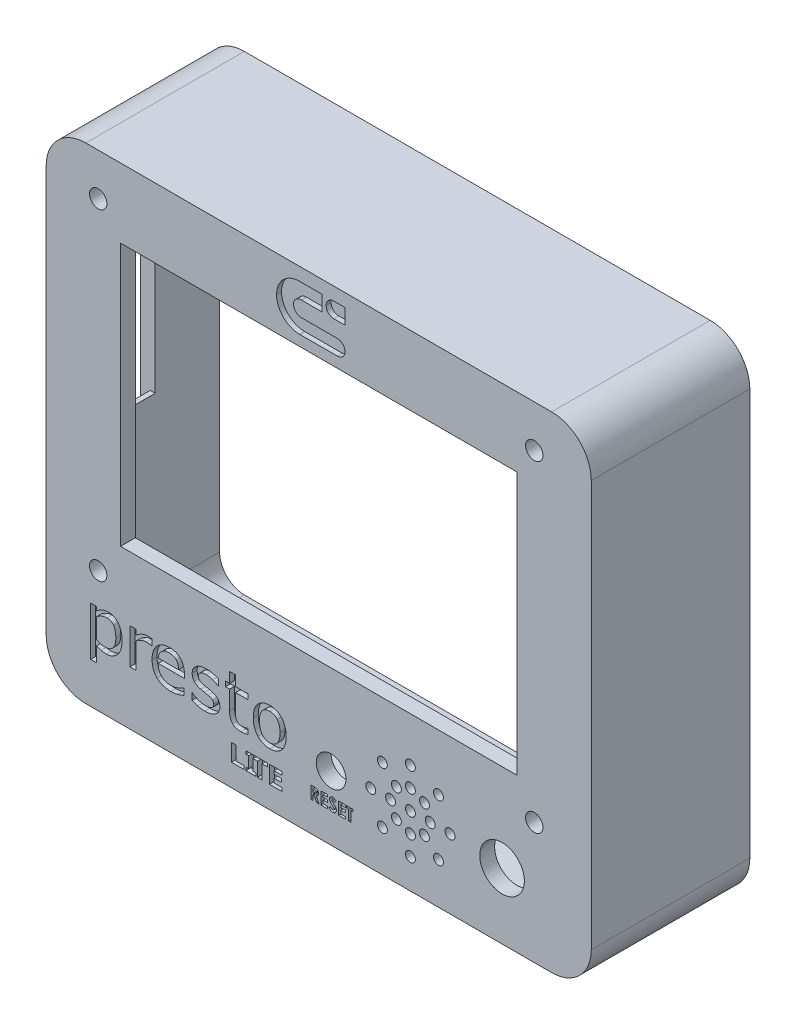
SolidWorks part; units mm, degrees
ref_plane "Plano frontal" through (0, 0, 0) normal (0, 0, 1) x (1, 0, 0)
ref_plane "Plano superior" through (0, 0, 0) normal (0, 1, 0) x (1, 0, 0)
ref_plane "Plano direito" through (0, 0, 0) normal (1, 0, 0) x (0, 0, -1)
sketch "Esboço1" plane through (0, 0, 0) normal (0, 0, 1) x (1, 0, 0)
  line L1 (55, 49) -> (-55, 49)
  line L3 (55, -49) -> (-55, -49)
  line L5 (55, 49) -> (-55, -49) construction
  line L6 (55, -49) -> (-55, 49) construction
  line L13 (-55, 0) -> (55, 0) construction
  line L14 (0, 49) -> (0, -49) construction
  line L38 (55, 49) -> (55, -49)
  line L40 (-55, 49) -> (-55, -49)
  point P0 (0, 0)
  dimension "D1" = 110
  dimension "D2" = 98
extrude "Ressalto-extrusão1" add sketch "Esboço1" along normal blind 22
fillet "Filete1" radius 8 4 edges at (-55, -49, 11) (55, -49, 11) (55, 49, 11) (-55, 49, 11)
shell "Casca1" thickness 3
sketch "Esboço2" plane through (0, 0, 22) normal (0, 0, 1) x (1, 0, 0)
  line L0 (-39, 34) -> (39, 34) construction
  line L1 (-39, 34) -> (-39, -17) construction
  line L2 (-39, -17) -> (39, -17) construction
  line L3 (39, 34) -> (39, -17) construction
  line L4 (-44.5, 40.5) -> (43.5, 40.5) construction
  line L5 (-44.5, 40.5) -> (-44.5, -24.5) construction
  line L6 (-44.5, -24.5) -> (43.5, -24.5) construction
  line L7 (43.5, 40.5) -> (43.5, -24.5) construction
  line L8 (-40, 35) -> (40, 35)
  line L9 (40, 35) -> (40, -18)
  line L10 (-40, -18) -> (40, -18)
  line L11 (-40, 35) -> (-40, -18)
  line L12 (0, 49) -> (0, 35) construction
  line L13 (47, 49) -> (-47, 49) construction
  line L14 (-44.5, 8) -> (43.5, 8) construction
  line L15 (0, 35) -> (0, -18) construction
  line L16 (-0.5, 40.5) -> (-0.5, -24.5) construction
  line L17 (-40, 8.5) -> (40, 8.5) construction
  circle A0 centre (37, -35.75) radius 4.5
  circle A1 centre (2.5, -36) radius 3
  circle A2 centre (-38.5, -33) radius 4 construction
  circle A3 centre (18.5, -35) radius 8
  circle A4 centre (-44.5, 40.5) radius 1.75
  circle A5 centre (43.5, 40.5) radius 1.75
  circle A6 centre (43.5, -24.5) radius 1.75
  circle A7 centre (-44.5, -24.5) radius 1.75
  dimension "D1" = 9
  dimension "D2" = 6
  dimension "D3" = 8
  dimension "D4" = 16
  dimension "D10" = 3.5
  dimension "D5" = 78
  dimension "D6" = 51
  dimension "D7" = 65
  dimension "D8" = 88
  dimension "D11" = 0.5
  dimension "D12" = 0.5
  dimension "D13" = 8.5
  dimension "D14" = 6
  dimension "D15" = 11.5
  dimension "D16" = 3
  dimension "D17" = 10.5
  dimension "D18" = 19
  dimension "D19" = 11.25
  dimension "D20" = 6.5
  dimension "D21" = 14
  dimension "D9" = 1
extrude "Corte-extrusão1" cut sketch "Esboço2" against normal through all contours L8 L11 L10 L9 | A4 | A5 | A6 | A0 | A1 | A2 | A7
sketch "Esboço3" plane through (0, 0, 22) normal (0, 0, 1) x (1, 0, 0)
  line L0 (10.5, -35) -> (26.5, -35) construction
  line L1 (18.5, -27) -> (18.5, -43) construction
  line L2 (12.8431, -40.6569) -> (24.1569, -29.3431) construction
  line L3 (24.1569, -40.6569) -> (12.8431, -29.3431) construction
  circle A0 centre (18.5, -35) radius 1
  circle A1 centre (18.5, -27) radius 1
  circle A2 centre (18.5, -35) radius 8 construction
  circle A3 centre (26.5, -35) radius 1
  circle A4 centre (18.5, -43) radius 1
  circle A5 centre (10.5, -35) radius 1
  circle A6 centre (12.8431, -29.3431) radius 1
  circle A7 centre (24.1569, -29.3431) radius 1
  circle A8 centre (24.1569, -40.6569) radius 1
  circle A9 centre (12.8431, -40.6569) radius 1
  circle A10 centre (18.5, -31) radius 1
  circle A11 centre (21.3284, -32.1716) radius 1
  circle A12 centre (22.5, -35) radius 1
  circle A13 centre (21.3284, -37.8284) radius 1
  circle A14 centre (18.5, -39) radius 1
  circle A15 centre (15.6716, -37.8284) radius 1
  circle A16 centre (14.5, -35) radius 1
  circle A17 centre (15.6716, -32.1716) radius 1
  circle A18 centre (18.5, -35) radius 4 construction
  dimension "D1" = 2
  dimension "D4" = 8
  dimension "D2" = 45
  dimension "D3" = 45
extrude "Corte-extrusão2" cut sketch "Esboço3" against normal blind 10
sketch "Esboço5" plane through (-55, 0, 0) normal (-1, 0, 0) x (0, 0, 1)
  line L0 (22, 8.25) -> (0, 8.25) construction
  line L1 (22, 41) -> (22, -41) construction
  line L2 (0, 41) -> (0, -41) construction
  line L3 (0, 49) -> (22, 49) construction
  line L4 (3, 23.25) -> (9, 23.25)
  line L5 (3, 23.25) -> (3, -6.75)
  line L6 (3, -6.75) -> (9, -6.75)
  line L7 (9, 23.25) -> (9, -6.75)
  line L8 (3, 23.25) -> (9, -6.75) construction
  line L9 (3, -6.75) -> (9, 23.25) construction
  point P8 (6, 8.25)
  dimension "D1" = 25.75
  dimension "D2" = 6
  dimension "D3" = 30
  dimension "D4" = 13
extrude "Corte-extrusão3" cut sketch "Esboço5" against normal blind 4
chamfer "Chanfro1" distance 2 angle 45 3 edges at (-55, -6.75, 6) (-55, 8.25, 9) (-55, 23.25, 6)
sketch "Esboço6" plane through (0, 0, 22) normal (0, 0, 1) x (1, 0, 0)
  line L0 (3.769, 40.2168) -> (0.4907, 40.2168)
  line L1 (0.4907, 40.2168) -> (-3.554, 40.2168)
  line L2 (-3.554, 40.2168) -> (-3.554, 40.2288)
  line L3 (-3.43, 43.3028) -> (0.4898, 43.3028)
  line L4 (0.4898, 43.3028) -> (0.627, 43.3028)
  line L5 (0.627, 43.3028) -> (0.627, 46.3891)
  line L6 (0.627, 46.3891) -> (-3.5708, 46.3891)
  line L7 (-3.5708, 46.3891) -> (-3.5708, 46.378)
  line L8 (-3.769, 37.1306) -> (3.769, 37.1306)
  line L9 (3.0324, 43.3028) -> (5.2847, 43.3028)
  line L10 (5.2847, 43.3028) -> (5.2847, 46.3891)
  line L11 (5.2847, 46.3891) -> (3.0324, 46.3891)
  line L85 (0, 0) -> (0, 56.1921) construction
  spline S0 degree 3 poles (-3.554, 40.2288) (-4.4007, 40.2332) (-5.086, 40.9206) (-5.086, 41.7685) knots 0 0 0 0 1 1 1 1
  spline S1 degree 3 poles (-5.086, 41.7685) (-5.086, 42.6191) (-4.3965, 43.3087) (-3.5458, 43.3087) knots 0 0 0 0 1 1 1 1
  spline S2 degree 3 poles (-3.5458, 43.3087) (-3.5067, 43.3087) (-3.4684, 43.3057) (-3.43, 43.3028) knots 0 0 0 0 1 1 1 1
  spline S3 degree 3 poles (-3.5708, 46.378) (-3.6718, 46.3846) (-3.7734, 46.3891) (-3.8761, 46.3891) knots 0 0 0 0 1 1 1 1
  spline S4 degree 3 poles (-3.8761, 46.3891) (-6.4335, 46.3891) (-8.5066, 44.3158) (-8.5066, 41.7585) knots 0 0 0 0 1 1 1 1
  spline S5 degree 3 poles (-8.5066, 41.7585) (-8.5066, 39.201) (-6.4335, 37.1279) (-3.8761, 37.1279) knots 0 0 0 0 1 1 1 1
  spline S6 degree 3 poles (-3.8761, 37.1279) (-3.8402, 37.1279) (-3.8048, 37.1298) (-3.769, 37.1306) knots 0 0 0 0 1 1 1 1
  spline S7 degree 3 poles (3.769, 37.1306) (4.6213, 37.1306) (5.3122, 37.8214) (5.3122, 38.6738) knots 0 0 0 0 1 1 1 1
  spline S8 degree 3 poles (5.3122, 38.6738) (5.3122, 39.5259) (4.6213, 40.2168) (3.769, 40.2168) knots 0 0 0 0 1 1 1 1
  spline S9 degree 3 poles (3.0324, 46.3891) (2.1802, 46.3891) (1.4893, 45.6981) (1.4893, 44.846) knots 0 0 0 0 1 1 1 1
  spline S10 degree 3 poles (1.4893, 44.846) (1.4893, 43.9937) (2.1802, 43.3028) (3.0324, 43.3028) knots 0 0 0 0 1 1 1 1
extrude "Corte-extrusão4" cut sketch "Esboço6" against normal blind 1
sketch "Esboço7" plane through (0, 0, 22) normal (0, 0, 1) x (1, 0, 0)
  line L12 (-44.8127, -37.7556) -> (-44.8127, -40.7697)
  line L13 (-44.8127, -40.7697) -> (-46.0235, -40.7697)
  line L14 (-46.0235, -40.7697) -> (-46.0235, -30.9222)
  line L15 (-46.0235, -30.9222) -> (-44.8127, -30.9222)
  line L16 (-44.8127, -30.9222) -> (-44.8127, -31.6757)
  line L17 (-44.8127, -32.6933) -> (-44.8127, -36.7702)
  line L18 (-33.6138, -32.2425) -> (-33.6782, -32.2425)
  line L19 (-36.892, -33.0089) -> (-36.892, -38.1162)
  line L20 (-36.892, -38.1162) -> (-38.1028, -38.1162)
  line L21 (-38.1028, -38.1162) -> (-38.1028, -30.9222)
  line L22 (-38.1028, -30.9222) -> (-36.892, -30.9222)
  line L23 (-36.892, -30.9222) -> (-36.892, -31.9849)
  line L24 (-33.6138, -30.9995) -> (-33.6138, -32.2425)
  line L25 (-27.0951, -34.6448) -> (-32.3956, -34.6448)
  line L26 (-27.3012, -36.358) -> (-27.2368, -36.358)
  line L27 (-27.2368, -36.358) -> (-27.2368, -37.6783)
  line L28 (-27.0951, -33.9879) -> (-27.0951, -34.6448)
  line L29 (-32.3956, -33.7174) -> (-28.2737, -33.7174)
  line L30 (-25.5672, -37.6847) -> (-25.5672, -36.3258)
  line L31 (-25.5672, -36.3258) -> (-25.5028, -36.3258)
  line L32 (-20.228, -31.2893) -> (-20.228, -32.5838)
  line L33 (-20.228, -32.5838) -> (-20.2924, -32.5838)
  line L34 (-17.9885, -35.7654) -> (-17.9885, -31.9398)
  line L35 (-17.9885, -31.9398) -> (-18.8064, -31.9398)
  line L36 (-18.8064, -31.9398) -> (-18.8064, -30.9222)
  line L37 (-18.8064, -30.9222) -> (-17.9885, -30.9222)
  line L38 (-17.9885, -30.9222) -> (-17.9885, -28.8548)
  line L39 (-17.9885, -28.8548) -> (-16.7776, -28.8548)
  line L40 (-16.7776, -28.8548) -> (-16.7776, -30.9222)
  line L41 (-16.7776, -30.9222) -> (-14.2787, -30.9222)
  line L42 (-14.2787, -30.9222) -> (-14.2787, -31.9398)
  line L43 (-14.2787, -31.9398) -> (-16.7776, -31.9398)
  line L44 (-16.7776, -31.9398) -> (-16.7776, -35.218)
  line L45 (-14.3431, -36.9634) -> (-14.2787, -36.9634)
  line L46 (-14.2787, -36.9634) -> (-14.2787, -38.0518)
  line L47 (-15.1161, -44.5456) -> (-17.6349, -44.5456)
  line L48 (-17.6349, -44.5456) -> (-17.6349, -41.0536)
  line L49 (-17.6349, -41.0536) -> (-16.7343, -41.0536)
  line L50 (-16.7343, -41.0536) -> (-16.7343, -43.8702)
  line L51 (-16.7343, -43.8702) -> (-15.1161, -43.8702)
  line L52 (-15.1161, -43.8702) -> (-15.1161, -44.5456)
  line L53 (-12.6635, -44.5456) -> (-14.7085, -44.5456)
  line L54 (-14.7085, -44.5456) -> (-14.7085, -43.9265)
  line L55 (-14.7085, -43.9265) -> (-14.1363, -43.9265)
  line L56 (-14.1363, -43.9265) -> (-14.1363, -41.6727)
  line L57 (-14.1363, -41.6727) -> (-14.7085, -41.6727)
  line L58 (-14.7085, -41.6727) -> (-14.7085, -41.0536)
  line L62 (-13.2357, -41.729) -> (-13.2357, -43.9265)
  line L63 (-13.2357, -43.9265) -> (-12.6635, -43.9265)
  line L64 (-12.6635, -43.9265) -> (-12.6635, -44.5456)
  line L65 (-10.3591, -41.729) -> (-11.4496, -41.729)
  line L66 (-11.4496, -41.729) -> (-11.4496, -44.5456)
  line L67 (-11.4496, -44.5456) -> (-12.3502, -44.5456)
  line L68 (-12.3502, -44.5456) -> (-12.3502, -41.729)
  line L69 (-12.3502, -41.729) -> (-13.2357, -41.729)
  line L71 (-14.7085, -41.0536) -> (-10.3591, -41.0536)
  line L72 (-10.3591, -41.0536) -> (-10.3591, -41.729)
  line L73 (-7.3907, -44.5456) -> (-9.9165, -44.5456)
  line L74 (-9.9165, -44.5456) -> (-9.9165, -41.0536)
  line L75 (-9.9165, -41.0536) -> (-7.3907, -41.0536)
  line L76 (-7.3907, -41.0536) -> (-7.3907, -41.729)
  line L77 (-7.3907, -41.729) -> (-9.0206, -41.729)
  line L78 (-9.0206, -41.729) -> (-9.0206, -42.3317)
  line L79 (-9.0206, -42.3317) -> (-7.508, -42.3317)
  line L80 (-7.508, -42.3317) -> (-7.508, -43.0071)
  line L81 (-7.508, -43.0071) -> (-9.0206, -43.0071)
  line L82 (-9.0206, -43.0071) -> (-9.0206, -43.8702)
  line L83 (-9.0206, -43.8702) -> (-7.3907, -43.8702)
  line L84 (-7.3907, -43.8702) -> (-7.3907, -44.5456)
  spline S11 degree 3 poles (-39.6925, -34.4323) (-39.6925, -35.0162) (-39.7763, -35.5508) (-39.9437, -36.0359) knots 0 0 0 0 1 1 1 1
  spline S12 degree 3 poles (-39.9437, -36.0359) (-40.1112, -36.5168) (-40.3473, -36.9247) (-40.6522, -37.2596) knots 0 0 0 0 1 1 1 1
  spline S13 degree 3 poles (-40.6522, -37.2596) (-40.9355, -37.5774) (-41.2705, -37.8243) (-41.6569, -38.0003) knots 0 0 0 0 1 1 1 1
  spline S14 degree 3 poles (-41.6569, -38.0003) (-42.039, -38.172) (-42.4448, -38.2579) (-42.8741, -38.2579) knots 0 0 0 0 1 1 1 1
  spline S15 degree 3 poles (-42.8741, -38.2579) (-43.2477, -38.2579) (-43.5869, -38.2171) (-43.8917, -38.1355) knots 0 0 0 0 1 1 1 1
  spline S16 degree 3 poles (-43.8917, -38.1355) (-44.1923, -38.054) (-44.4993, -37.9273) (-44.8127, -37.7556) knots 0 0 0 0 1 1 1 1
  spline S17 degree 3 poles (-44.8127, -31.6757) (-44.4907, -31.4052) (-44.13, -31.1798) (-43.7307, -30.9995) knots 0 0 0 0 1 1 1 1
  spline S18 degree 3 poles (-43.7307, -30.9995) (-43.3271, -30.8148) (-42.8978, -30.7225) (-42.4426, -30.7225) knots 0 0 0 0 1 1 1 1
  spline S19 degree 3 poles (-42.4426, -30.7225) (-41.5753, -30.7225) (-40.9012, -31.051) (-40.4203, -31.7079) knots 0 0 0 0 1 1 1 1
  spline S20 degree 3 poles (-40.4203, -31.7079) (-39.9351, -32.3606) (-39.6925, -33.2687) (-39.6925, -34.4323) knots 0 0 0 0 1 1 1 1
  spline S21 degree 3 poles (-40.942, -34.4645) (-40.942, -33.5971) (-41.0901, -32.9488) (-41.3864, -32.5194) knots 0 0 0 0 1 1 1 1
  spline S22 degree 3 poles (-41.3864, -32.5194) (-41.6826, -32.0901) (-42.1378, -31.8754) (-42.7518, -31.8754) knots 0 0 0 0 1 1 1 1
  spline S23 degree 3 poles (-42.7518, -31.8754) (-43.0996, -31.8754) (-43.4495, -31.9505) (-43.8016, -32.1008) knots 0 0 0 0 1 1 1 1
  spline S24 degree 3 poles (-43.8016, -32.1008) (-44.1536, -32.2511) (-44.4907, -32.4486) (-44.8127, -32.6933) knots 0 0 0 0 1 1 1 1
  spline S25 degree 3 poles (-44.8127, -36.7702) (-44.4692, -36.9247) (-44.1751, -37.0299) (-43.9304, -37.0857) knots 0 0 0 0 1 1 1 1
  spline S26 degree 3 poles (-43.9304, -37.0857) (-43.6813, -37.1416) (-43.4001, -37.1695) (-43.0867, -37.1695) knots 0 0 0 0 1 1 1 1
  spline S27 degree 3 poles (-43.0867, -37.1695) (-42.4126, -37.1695) (-41.8866, -36.9419) (-41.5088, -36.4868) knots 0 0 0 0 1 1 1 1
  spline S28 degree 3 poles (-41.5088, -36.4868) (-41.1309, -36.0316) (-40.942, -35.3575) (-40.942, -34.4645) knots 0 0 0 0 1 1 1 1
  spline S29 degree 3 poles (-33.6782, -32.2425) (-33.8585, -32.1996) (-34.0345, -32.1695) (-34.2063, -32.1523) knots 0 0 0 0 1 1 1 1
  spline S30 degree 3 poles (-34.2063, -32.1523) (-34.3737, -32.1309) (-34.5734, -32.1201) (-34.8053, -32.1201) knots 0 0 0 0 1 1 1 1
  spline S31 degree 3 poles (-34.8053, -32.1201) (-35.1788, -32.1201) (-35.5395, -32.2038) (-35.8873, -32.3713) knots 0 0 0 0 1 1 1 1
  spline S32 degree 3 poles (-35.8873, -32.3713) (-36.235, -32.5345) (-36.57, -32.747) (-36.892, -33.0089) knots 0 0 0 0 1 1 1 1
  spline S33 degree 3 poles (-36.892, -31.9849) (-36.4111, -31.5984) (-35.9882, -31.3258) (-35.6232, -31.1669) knots 0 0 0 0 1 1 1 1
  spline S34 degree 3 poles (-35.6232, -31.1669) (-35.2539, -31.0038) (-34.8783, -30.9222) (-34.4961, -30.9222) knots 0 0 0 0 1 1 1 1
  spline S35 degree 3 poles (-34.4961, -30.9222) (-34.2857, -30.9222) (-34.1333, -30.9286) (-34.0388, -30.9415) knots 0 0 0 0 1 1 1 1
  spline S36 degree 3 poles (-34.0388, -30.9415) (-33.9444, -30.9501) (-33.8027, -30.9694) (-33.6138, -30.9995) knots 0 0 0 0 1 1 1 1
  spline S37 degree 3 poles (-32.3956, -34.6448) (-32.3956, -35.087) (-32.329, -35.4735) (-32.1959, -35.8041) knots 0 0 0 0 1 1 1 1
  spline S38 degree 3 poles (-32.1959, -35.8041) (-32.0628, -36.1304) (-31.8803, -36.3988) (-31.6485, -36.6091) knots 0 0 0 0 1 1 1 1
  spline S39 degree 3 poles (-31.6485, -36.6091) (-31.4252, -36.8152) (-31.1612, -36.9698) (-30.8563, -37.0729) knots 0 0 0 0 1 1 1 1
  spline S40 degree 3 poles (-30.8563, -37.0729) (-30.5472, -37.1759) (-30.208, -37.2274) (-29.8387, -37.2274) knots 0 0 0 0 1 1 1 1
  spline S41 degree 3 poles (-29.8387, -37.2274) (-29.3492, -37.2274) (-28.8576, -37.1308) (-28.3638, -36.9376) knots 0 0 0 0 1 1 1 1
  spline S42 degree 3 poles (-28.3638, -36.9376) (-27.8658, -36.7401) (-27.5115, -36.5469) (-27.3012, -36.358) knots 0 0 0 0 1 1 1 1
  spline S43 degree 3 poles (-27.2368, -37.6783) (-27.6446, -37.85) (-28.0611, -37.9939) (-28.4862, -38.1098) knots 0 0 0 0 1 1 1 1
  spline S44 degree 3 poles (-28.4862, -38.1098) (-28.9113, -38.2257) (-29.3578, -38.2837) (-29.8258, -38.2837) knots 0 0 0 0 1 1 1 1
  spline S45 degree 3 poles (-29.8258, -38.2837) (-31.0195, -38.2837) (-31.9512, -37.9616) (-32.621, -37.3176) knots 0 0 0 0 1 1 1 1
  spline S46 degree 3 poles (-32.621, -37.3176) (-33.2908, -36.6693) (-33.6257, -35.7504) (-33.6257, -34.5611) knots 0 0 0 0 1 1 1 1
  spline S47 degree 3 poles (-33.6257, -34.5611) (-33.6257, -33.3846) (-33.3058, -32.4507) (-32.6661, -31.7595) knots 0 0 0 0 1 1 1 1
  spline S48 degree 3 poles (-32.6661, -31.7595) (-32.022, -31.0682) (-31.1762, -30.7225) (-30.1285, -30.7225) knots 0 0 0 0 1 1 1 1
  spline S49 degree 3 poles (-30.1285, -30.7225) (-29.1582, -30.7225) (-28.4111, -31.0059) (-27.8872, -31.5727) knots 0 0 0 0 1 1 1 1
  spline S50 degree 3 poles (-27.8872, -31.5727) (-27.3591, -32.1394) (-27.0951, -32.9445) (-27.0951, -33.9879) knots 0 0 0 0 1 1 1 1
  spline S51 degree 3 poles (-28.2737, -33.7174) (-28.278, -33.0819) (-28.439, -32.5903) (-28.7567, -32.2425) knots 0 0 0 0 1 1 1 1
  spline S52 degree 3 poles (-28.7567, -32.2425) (-29.0701, -31.8947) (-29.5489, -31.7208) (-30.1929, -31.7208) knots 0 0 0 0 1 1 1 1
  spline S53 degree 3 poles (-30.1929, -31.7208) (-30.8413, -31.7208) (-31.3587, -31.9119) (-31.7451, -32.294) knots 0 0 0 0 1 1 1 1
  spline S54 degree 3 poles (-31.7451, -32.294) (-32.1272, -32.6761) (-32.3441, -33.1506) (-32.3956, -33.7174) knots 0 0 0 0 1 1 1 1
  spline S55 degree 3 poles (-19.9446, -36.0424) (-19.9446, -36.6993) (-20.2173, -37.2382) (-20.7626, -37.6589) knots 0 0 0 0 1 1 1 1
  spline S56 degree 3 poles (-20.7626, -37.6589) (-21.3036, -38.0797) (-22.0442, -38.2901) (-22.9845, -38.2901) knots 0 0 0 0 1 1 1 1
  spline S57 degree 3 poles (-22.9845, -38.2901) (-23.5169, -38.2901) (-24.0064, -38.2279) (-24.453, -38.1033) knots 0 0 0 0 1 1 1 1
  spline S58 degree 3 poles (-24.453, -38.1033) (-24.8952, -37.9745) (-25.2666, -37.835) (-25.5672, -37.6847) knots 0 0 0 0 1 1 1 1
  spline S59 degree 3 poles (-25.5028, -36.3258) (-25.1206, -36.6134) (-24.6956, -36.8432) (-24.2275, -37.0149) knots 0 0 0 0 1 1 1 1
  spline S60 degree 3 poles (-24.2275, -37.0149) (-23.7595, -37.1823) (-23.3108, -37.2661) (-22.8815, -37.2661) knots 0 0 0 0 1 1 1 1
  spline S61 degree 3 poles (-22.8815, -37.2661) (-22.3491, -37.2661) (-21.9326, -37.1802) (-21.632, -37.0085) knots 0 0 0 0 1 1 1 1
  spline S62 degree 3 poles (-21.632, -37.0085) (-21.3315, -36.8367) (-21.1812, -36.5662) (-21.1812, -36.197) knots 0 0 0 0 1 1 1 1
  spline S63 degree 3 poles (-21.1812, -36.197) (-21.1812, -35.9136) (-21.2628, -35.6989) (-21.4259, -35.5529) knots 0 0 0 0 1 1 1 1
  spline S64 degree 3 poles (-21.4259, -35.5529) (-21.5891, -35.4069) (-21.9025, -35.2824) (-22.3662, -35.1794) knots 0 0 0 0 1 1 1 1
  spline S65 degree 3 poles (-22.3662, -35.1794) (-22.538, -35.1407) (-22.7634, -35.0956) (-23.0425, -35.0441) knots 0 0 0 0 1 1 1 1
  spline S66 degree 3 poles (-23.0425, -35.0441) (-23.3173, -34.9926) (-23.5685, -34.9368) (-23.796, -34.8767) knots 0 0 0 0 1 1 1 1
  spline S67 degree 3 poles (-23.796, -34.8767) (-24.4272, -34.7092) (-24.8759, -34.4645) (-25.1421, -34.1424) knots 0 0 0 0 1 1 1 1
  spline S68 degree 3 poles (-25.1421, -34.1424) (-25.404, -33.8161) (-25.535, -33.4168) (-25.535, -32.9445) knots 0 0 0 0 1 1 1 1
  spline S69 degree 3 poles (-25.535, -32.9445) (-25.535, -32.6482) (-25.4749, -32.3692) (-25.3546, -32.1072) knots 0 0 0 0 1 1 1 1
  spline S70 degree 3 poles (-25.3546, -32.1072) (-25.2301, -31.8453) (-25.0433, -31.6113) (-24.7943, -31.4052) knots 0 0 0 0 1 1 1 1
  spline S71 degree 3 poles (-24.7943, -31.4052) (-24.5539, -31.2034) (-24.249, -31.0446) (-23.8798, -30.9286) knots 0 0 0 0 1 1 1 1
  spline S72 degree 3 poles (-23.8798, -30.9286) (-23.5062, -30.8084) (-23.0897, -30.7483) (-22.6303, -30.7483) knots 0 0 0 0 1 1 1 1
  spline S73 degree 3 poles (-22.6303, -30.7483) (-22.2009, -30.7483) (-21.7673, -30.802) (-21.3293, -30.9093) knots 0 0 0 0 1 1 1 1
  spline S74 degree 3 poles (-21.3293, -30.9093) (-20.8871, -31.0124) (-20.52, -31.139) (-20.228, -31.2893) knots 0 0 0 0 1 1 1 1
  spline S75 degree 3 poles (-20.2924, -32.5838) (-20.6015, -32.3563) (-20.9772, -32.1652) (-21.4195, -32.0106) knots 0 0 0 0 1 1 1 1
  spline S76 degree 3 poles (-21.4195, -32.0106) (-21.8617, -31.8518) (-22.2954, -31.7723) (-22.7205, -31.7723) knots 0 0 0 0 1 1 1 1
  spline S77 degree 3 poles (-22.7205, -31.7723) (-23.1627, -31.7723) (-23.5363, -31.8582) (-23.8411, -32.03) knots 0 0 0 0 1 1 1 1
  spline S78 degree 3 poles (-23.8411, -32.03) (-24.146, -32.1974) (-24.2984, -32.4486) (-24.2984, -32.7835) knots 0 0 0 0 1 1 1 1
  spline S79 degree 3 poles (-24.2984, -32.7835) (-24.2984, -33.0798) (-24.2061, -33.303) (-24.0215, -33.4533) knots 0 0 0 0 1 1 1 1
  spline S80 degree 3 poles (-24.0215, -33.4533) (-23.8411, -33.6036) (-23.5491, -33.726) (-23.1455, -33.8204) knots 0 0 0 0 1 1 1 1
  spline S81 degree 3 poles (-23.1455, -33.8204) (-22.9223, -33.8719) (-22.6732, -33.9235) (-22.3984, -33.975) knots 0 0 0 0 1 1 1 1
  spline S82 degree 3 poles (-22.3984, -33.975) (-22.1194, -34.0265) (-21.8875, -34.0737) (-21.7029, -34.1167) knots 0 0 0 0 1 1 1 1
  spline S83 degree 3 poles (-21.7029, -34.1167) (-21.1404, -34.2455) (-20.7067, -34.4666) (-20.4019, -34.78) knots 0 0 0 0 1 1 1 1
  spline S84 degree 3 poles (-20.4019, -34.78) (-20.097, -35.0978) (-19.9446, -35.5186) (-19.9446, -36.0424) knots 0 0 0 0 1 1 1 1
  spline S85 degree 3 poles (-14.2787, -38.0518) (-14.5063, -38.1119) (-14.7553, -38.1613) (-15.0258, -38.1999) knots 0 0 0 0 1 1 1 1
  spline S86 degree 3 poles (-15.0258, -38.1999) (-15.292, -38.2386) (-15.5303, -38.2579) (-15.7407, -38.2579) knots 0 0 0 0 1 1 1 1
  spline S87 degree 3 poles (-15.7407, -38.2579) (-16.4749, -38.2579) (-17.0331, -38.0604) (-17.4153, -37.6654) knots 0 0 0 0 1 1 1 1
  spline S88 degree 3 poles (-17.4153, -37.6654) (-17.7974, -37.2704) (-17.9885, -36.6371) (-17.9885, -35.7654) knots 0 0 0 0 1 1 1 1
  spline S89 degree 3 poles (-16.7776, -35.218) (-16.7776, -35.5958) (-16.7691, -35.8921) (-16.7519, -36.1068) knots 0 0 0 0 1 1 1 1
  spline S90 degree 3 poles (-16.7519, -36.1068) (-16.7347, -36.3172) (-16.6746, -36.5147) (-16.5715, -36.6993) knots 0 0 0 0 1 1 1 1
  spline S91 degree 3 poles (-16.5715, -36.6993) (-16.4771, -36.8711) (-16.3483, -36.9977) (-16.1851, -37.0793) knots 0 0 0 0 1 1 1 1
  spline S92 degree 3 poles (-16.1851, -37.0793) (-16.0177, -37.1566) (-15.7643, -37.1952) (-15.4251, -37.1952) knots 0 0 0 0 1 1 1 1
  spline S93 degree 3 poles (-15.4251, -37.1952) (-15.2276, -37.1952) (-15.0215, -37.1673) (-14.8069, -37.1115) knots 0 0 0 0 1 1 1 1
  spline S94 degree 3 poles (-14.8069, -37.1115) (-14.5922, -37.0514) (-14.4376, -37.002) (-14.3431, -36.9634) knots 0 0 0 0 1 1 1 1
  spline S95 degree 3 poles (-6.5672, -34.5224) (-6.5672, -35.6946) (-6.8678, -36.6199) (-7.4689, -37.2983) knots 0 0 0 0 1 1 1 1
  spline S96 degree 3 poles (-7.4689, -37.2983) (-8.07, -37.9767) (-8.8751, -38.3159) (-9.8841, -38.3159) knots 0 0 0 0 1 1 1 1
  spline S97 degree 3 poles (-9.8841, -38.3159) (-10.9017, -38.3159) (-11.7111, -37.9767) (-12.3122, -37.2983) knots 0 0 0 0 1 1 1 1
  spline S98 degree 3 poles (-12.3122, -37.2983) (-12.909, -36.6199) (-13.2074, -35.6946) (-13.2074, -34.5224) knots 0 0 0 0 1 1 1 1
  spline S99 degree 3 poles (-13.2074, -34.5224) (-13.2074, -33.3503) (-12.909, -32.425) (-12.3122, -31.7466) knots 0 0 0 0 1 1 1 1
  spline S100 degree 3 poles (-12.3122, -31.7466) (-11.7111, -31.0639) (-10.9017, -30.7225) (-9.8841, -30.7225) knots 0 0 0 0 1 1 1 1
  spline S101 degree 3 poles (-9.8841, -30.7225) (-8.8751, -30.7225) (-8.07, -31.0639) (-7.4689, -31.7466) knots 0 0 0 0 1 1 1 1
  spline S102 degree 3 poles (-7.4689, -31.7466) (-6.8678, -32.425) (-6.5672, -33.3503) (-6.5672, -34.5224) knots 0 0 0 0 1 1 1 1
  spline S103 degree 3 poles (-7.8167, -34.5224) (-7.8167, -33.5907) (-7.9992, -32.8994) (-8.3641, -32.4486) knots 0 0 0 0 1 1 1 1
  spline S104 degree 3 poles (-8.3641, -32.4486) (-8.7291, -31.9935) (-9.2358, -31.7659) (-9.8841, -31.7659) knots 0 0 0 0 1 1 1 1
  spline S105 degree 3 poles (-9.8841, -31.7659) (-10.541, -31.7659) (-11.052, -31.9935) (-11.4169, -32.4486) knots 0 0 0 0 1 1 1 1
  spline S106 degree 3 poles (-11.4169, -32.4486) (-11.7776, -32.8994) (-11.9579, -33.5907) (-11.9579, -34.5224) knots 0 0 0 0 1 1 1 1
  spline S107 degree 3 poles (-11.9579, -34.5224) (-11.9579, -35.4241) (-11.7755, -36.1089) (-11.4105, -36.5769) knots 0 0 0 0 1 1 1 1
  spline S108 degree 3 poles (-11.4105, -36.5769) (-11.0455, -37.0407) (-10.5367, -37.2725) (-9.8841, -37.2725) knots 0 0 0 0 1 1 1 1
  spline S109 degree 3 poles (-9.8841, -37.2725) (-9.24, -37.2725) (-8.7355, -37.0428) (-8.3706, -36.5834) knots 0 0 0 0 1 1 1 1
  spline S110 degree 3 poles (-8.3706, -36.5834) (-8.0013, -36.1197) (-7.8167, -35.4327) (-7.8167, -34.5224) knots 0 0 0 0 1 1 1 1
extrude "Corte-extrusão5" cut sketch "Esboço7" against normal blind 1
sketch "Esboço8" plane through (0, 0, 22) normal (0, 0, 1) x (1, 0, 0)
  line L0 (2.5, -30) -> (2.5, -29) construction
  line L1 (2.5, -29) -> (5, -30.75) construction
  line L2 (5, -30.75) -> (2.5, -32.5) construction
  line L3 (2.5, -32.5) -> (2.5, -31.5) construction
  line L4 (2.5, -30) -> (2.5, -31.5) construction
  line L5 (2.5, -30.75) -> (5, -30.75) construction
  line L6 (7, -36) -> (8.5, -36) construction
  line L7 (-1.8676, -43) -> (6.9652, -43) construction
  line L8 (2.5, -36) -> (2.5488, -43) construction
  arc A0 (2.5, -30) -> (8.5, -36) centre (2.5, -36) ccw construction
  arc A1 (2.5, -31.5) -> (7, -36) centre (2.5, -36) ccw construction
  circle A2 centre (2.5, -36) radius 6 construction
  circle A3 centre (2.5, -36) radius 4.5 construction
  text T0 "RESET" font "Century Gothic" height 2.5
  dimension "D1" = 12
  dimension "D3" = 1
  dimension "D4" = 2.5
  dimension "D5" = 7
  dimension "D2" = 1.5
extrude "Corte-extrusão6" cut sketch "Esboço8" against normal blind 1
sketch "Esboço9" plane through (0, 0, 0) normal (0, 0, -1) x (-1, 0, 0)
  line L1 (-52, 41) -> (-52, -41) construction
  line L4 (-47, -49) -> (47, -49)
  line L5 (55, -41) -> (55, 41)
  line L6 (47, 49) -> (-47, 49)
  line L7 (-55, 41) -> (-55, -41)
  line L8 (-47, -49) -> (47, -49)
  line L9 (55, -41) -> (55, 41)
  line L10 (47, 49) -> (-47, 49)
  line L11 (-55, 41) -> (-55, -41)
  line L12 (-47, 46) -> (47, 46) construction
  line L13 (-47, -46) -> (47, -46) construction
  line L14 (52, 41) -> (52, -41) construction
  line L15 (-47, 46) -> (47, 46)
  line L16 (-52, 41) -> (-52, -41)
  line L17 (-47, -46) -> (47, -46)
  line L18 (52, 41) -> (52, -41)
  arc A0 (-47, 46) -> (-52, 41) centre (-47, 41) ccw construction
  arc A1 (-52, -41) -> (-47, -46) centre (-47, -41) ccw construction
  arc A2 (47, -46) -> (52, -41) centre (47, -41) ccw construction
  arc A3 (52, 41) -> (47, 46) centre (47, 41) ccw construction
  arc A4 (47, -49) -> (55, -41) centre (47, -41) ccw
  arc A5 (55, 41) -> (47, 49) centre (47, 41) ccw
  arc A6 (-47, 49) -> (-55, 41) centre (-47, 41) ccw
  arc A7 (-55, -41) -> (-47, -49) centre (-47, -41) ccw
  arc A8 (47, -49) -> (55, -41) centre (47, -41) ccw
  arc A9 (55, 41) -> (47, 49) centre (47, 41) ccw
  arc A10 (-47, 49) -> (-55, 41) centre (-47, 41) ccw
  arc A11 (-55, -41) -> (-47, -49) centre (-47, -41) ccw
  arc A12 (-47, 46) -> (-52, 41) centre (-47, 41) ccw
  arc A13 (-52, -41) -> (-47, -46) centre (-47, -41) ccw
  arc A14 (47, -46) -> (52, -41) centre (47, -41) ccw
  arc A15 (52, 41) -> (47, 46) centre (47, 41) ccw
  dimension "D1" = 0
extrude "Ressalto-extrusão2" add sketch "Esboço9" along normal blind 10
